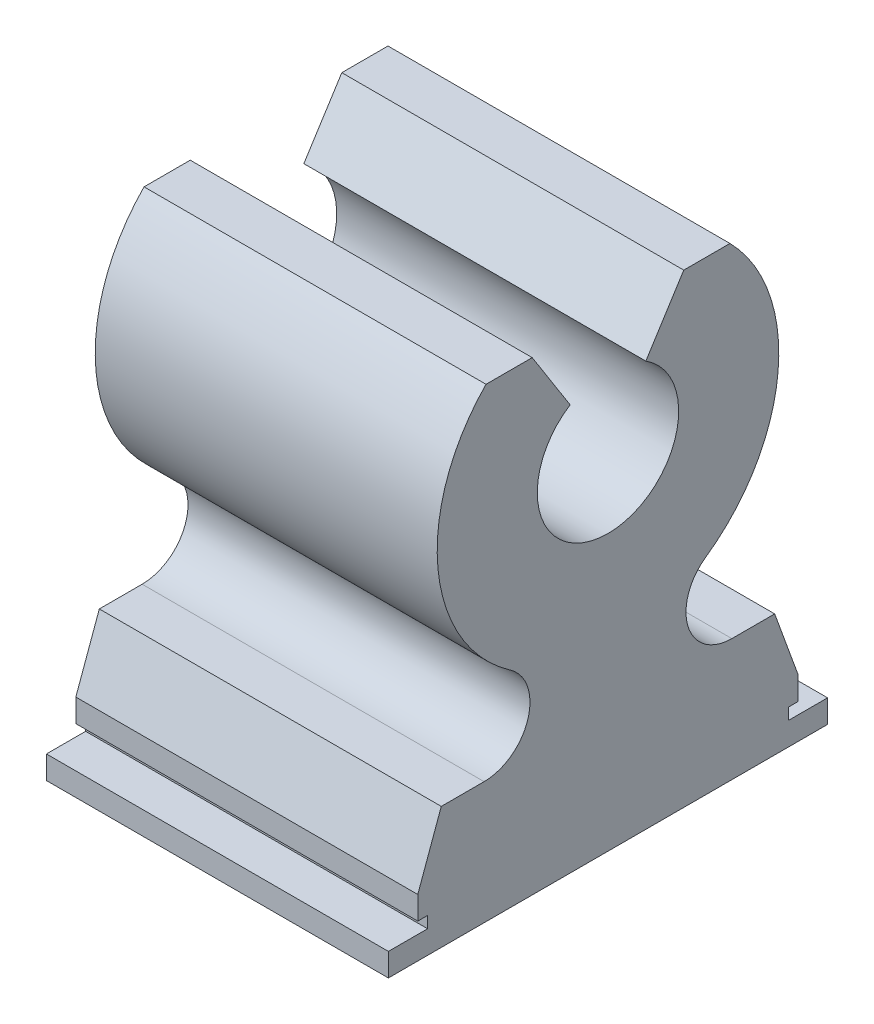
SolidWorks part; units mm, degrees
ref_plane "Plane1" through (0, 0, 0) normal (0, 0, 1) x (1, 0, 0)
ref_plane "Plane2" through (0, 0, 0) normal (0, 1, 0) x (1, 0, 0)
ref_plane "Plane3" through (0, 0, 0) normal (1, 0, 0) x (0, 0, -1)
sketch "BodySke" plane through (0, 0, 0) normal (1, 0, 0) x (0, 0, -1)
  line L0 (-5.715, -9) -> (5.715, -9)
  line L1 (5.715, -9) -> (5.715, -8.4)
  line L2 (5.715, -8.4) -> (4.695, -8.4)
  line L3 (-5.715, -9) -> (-5.715, -8.4)
  line L4 (-5.715, -8.4) -> (-4.695, -8.4)
  line L5 (4.695, -8.4) -> (4.695, -8.1)
  line L6 (-4.695, -8.4) -> (-4.695, -8.1)
  line L7 (4.695, -8.1) -> (4.95, -8.1)
  line L8 (-4.695, -8.1) -> (-4.95, -8.1)
  line L9 (-3.2237, -5.82) -> (-4.3385, -5.82)
  line L11 (4.3385, -5.82) -> (3.2237, -5.82)
  line L12 (0, 7.62) -> (0, -11.43) construction
  line L13 (7.62, 0) -> (-7.62, 0) construction
  line L14 (2.03, -2.8908) -> (2.03, -7.62) construction
  line L15 (-2.03, -2.8908) -> (-2.03, -7.62) construction
  line L16 (4.3385, -5.82) -> (4.95, -7.5)
  line L17 (4.95, -7.5) -> (4.95, -8.1)
  line L18 (-4.3385, -5.82) -> (-4.95, -7.5)
  line L19 (-4.95, -7.5) -> (-4.95, -8.1)
  line L20 (-0.985, 1.5541) -> (-2.3795, 3.7544)
  line L21 (0.985, 1.5541) -> (2.3795, 3.7544)
  arc A0 (-0.985, 1.5541) -> (0.985, 1.5541) centre (0, 0) ccw
  arc A1 (2.5412, -3.6469) -> (2.3795, 3.7544) centre (0, 0) ccw
  arc A2 (3.2237, -5.82) -> (2.5412, -3.6469) centre (3.2237, -4.6263) cw
  arc A3 (-2.5412, -3.6469) -> (-3.2237, -5.82) centre (-3.2237, -4.6263) cw
  arc A4 (-2.3795, 3.7544) -> (-2.5412, -3.6469) centre (0, 0) ccw
  dimension "Thread_min" = 3.68
  dimension "C_dia" = 8.89
  dimension "J_dim" = 4.06
  dimension "E_dim" = 11.43
  dimension "D_dim" = 3.18
  dimension "Clinch_ht" = 0.6
  dimension "Side_ht" = 0.6
  dimension "Groove_wid" = 0.3
  dimension "A_dim" = 9.9
  dimension "Groove_overall" = 9.39
  dimension "F_dim" = 9
  dimension "D12" = 20
  dimension "H_dim" = 1.97
extrude "Body" add sketch "BodySke" along normal blind 8.9
cosmetic thread "ThreadCosmetic" [suppressed] parameters "Thread_nominal"=4.1656
sketch "TopCutSke" plane through (0, 0, 0) normal (-1, 0, 0) x (0, 0, 1)
  line L0 (0, 0) -> (0, 6.35) construction
  line L1 (-4.445, 3.1115) -> (4.445, 3.1115)
  line L2 (-4.445, 3.1115) -> (-4.445, 12.0015)
  line L3 (-4.445, 12.0015) -> (4.445, 12.0015)
  line L4 (4.445, 3.1115) -> (4.445, 12.0015)
  dimension "Offset" = 3.1115
  dimension "Width" = 8.89
extrude "TopCut" cut sketch "TopCutSke" against normal blind 8.9
equation "' \"Length@Body\" = 8.9"
equation "' \"A_dim@BodySke\" = 9.9"
equation "' \"C_dia@BodySke\" = 8.89"
equation "' \"D_dim@BodySke\" = 3.18"
equation "' \"E_dim@BodySke\" = 11.43"
equation "' \"F_dim@BodySke\" = 9"
equation "' \"H_dim@BodySke\" = 1.97"
equation "' \"J_dim@BodySke\" =  4.06"
equation "' \"J_dim@BodySke\" = 4.06"
equation "' \"Thread_min@BodySke\" = 3.68"
equation "\"Width@TopCutSke\" = \"C_dia@BodySke\""
equation "\"Offset@TopCutSke\" = \"C_dia@BodySke\" * 0.35"
equation "\"Length@TopCut\" = \"Length@Body\""
equation "\"Clinch_ht@BodySke\" = 1 * 0.6"
equation "\"Groove_wid@BodySke\" = \"Clinch_ht@BodySke\" / 2"
equation "\"Groove_overall@BodySke\" = \"A_dim@BodySke\" - ( \"E_dim@BodySke\" - \"A_dim@BodySke\") / 3"
equation "\"Side_ht@BodySke\" = \"Clinch_ht@BodySke\""
